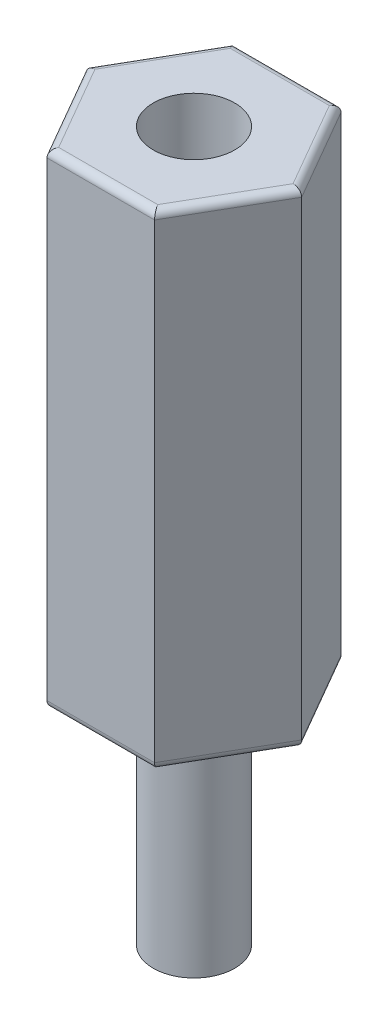
SolidWorks part; units mm, degrees
material "201.0-T43 Molde de fundição com isolamento (SS)"
ref_plane "Plano frontal" through (0, 0, 0) normal (0, 0, 1) x (1, 0, 0)
ref_plane "Plano superior" through (0, 0, 0) normal (0, 1, 0) x (1, 0, 0)
ref_plane "Plano direito" through (0, 0, 0) normal (1, 0, 0) x (0, 0, -1)
sketch "Esboço1" plane through (0, 0, 0) normal (0, 1, 0) x (1, 0, 0)
  line L1 (2.8868, 0) -> (1.4434, 2.5)
  line L2 (1.4434, 2.5) -> (-1.4434, 2.5)
  line L3 (-1.4434, 2.5) -> (-2.8868, 0)
  line L4 (-2.8868, 0) -> (-1.4434, -2.5)
  line L5 (-1.4434, -2.5) -> (1.4434, -2.5)
  line L6 (1.4434, -2.5) -> (2.8868, 0)
  circle A0 centre (0, 0) radius 2.5 construction
  dimension "D1" = 5
extrude "Ressalto-extrusão1" add sketch "Esboço1" along normal blind 13
fillet "Filete1" radius 0.2 12 edges at (0, 13, -2.5) (-2.1651, 13, -1.25) (-2.1651, 13, 1.25) (0, 13, 2.5) (2.1651, 13, 1.25) (2.1651, 13, -1.25) (0, 0, 2.5) (-2.1651, 0, 1.25) (-2.1651, 0, -1.25) (0, 0, -2.5) (2.1651, 0, -1.25) (2.1651, 0, 1.25)
sketch "Esboço2" plane through (0, 0, 0) normal (0, -1, 0) x (1, 0, 0)
  circle A0 centre (0, 0) radius 1.0922
  dimension "D1" = 2.1844
extrude "Ressalto-extrusão2" add sketch "Esboço2" along normal blind 6
sketch "Esboço3" plane through (0, 13, 0) normal (0, 1, 0) x (1, 0, 0)
  circle A0 centre (0, 0) radius 1.0922
extrude "Corte-extrusão1" cut sketch "Esboço3" against normal blind 4.76
